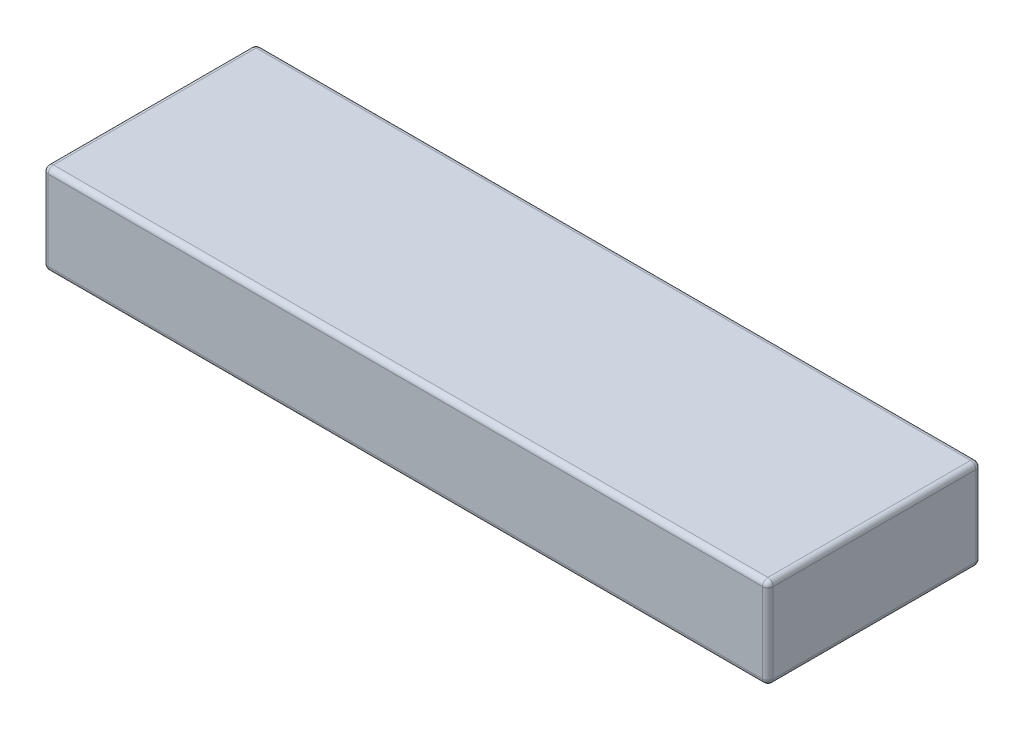
SolidWorks part; units mm, degrees
ref_plane "前视基准面" through (0, 0, 0) normal (0, 0, 1) x (1, 0, 0)
ref_plane "上视基准面" through (0, 0, 0) normal (0, 1, 0) x (1, 0, 0)
ref_plane "右视基准面" through (0, 0, 0) normal (1, 0, 0) x (0, 0, -1)
other "Configuration Table"
sketch "草图1" plane through (0, 0, 0) normal (0, 1, 0) x (1, 0, 0)
  line L1 (-68, -20) -> (68, -20)
  line L2 (-68, -20) -> (-68, 20)
  line L3 (-68, 20) -> (68, 20)
  line L4 (68, -20) -> (68, 20)
  line L5 (-68, -20) -> (68, 20) construction
  line L6 (-68, 20) -> (68, -20) construction
  point P0 (0, 0)
  dimension "D1" = 40
  dimension "D2" = 136
extrude "凸台-拉伸1" add sketch "草图1" along normal blind 17
fillet "圆角1" radius 1 12 edges at (0, 0, -20) (-68, 0, 0) (0, 0, 20) (68, 0, 0) (0, 17, 20) (-68, 17, 0) (0, 17, -20) (68, 17, 0) (68, 8.5, 20) (-68, 8.5, -20) (68, 8.5, -20) (-68, 8.5, 20)
